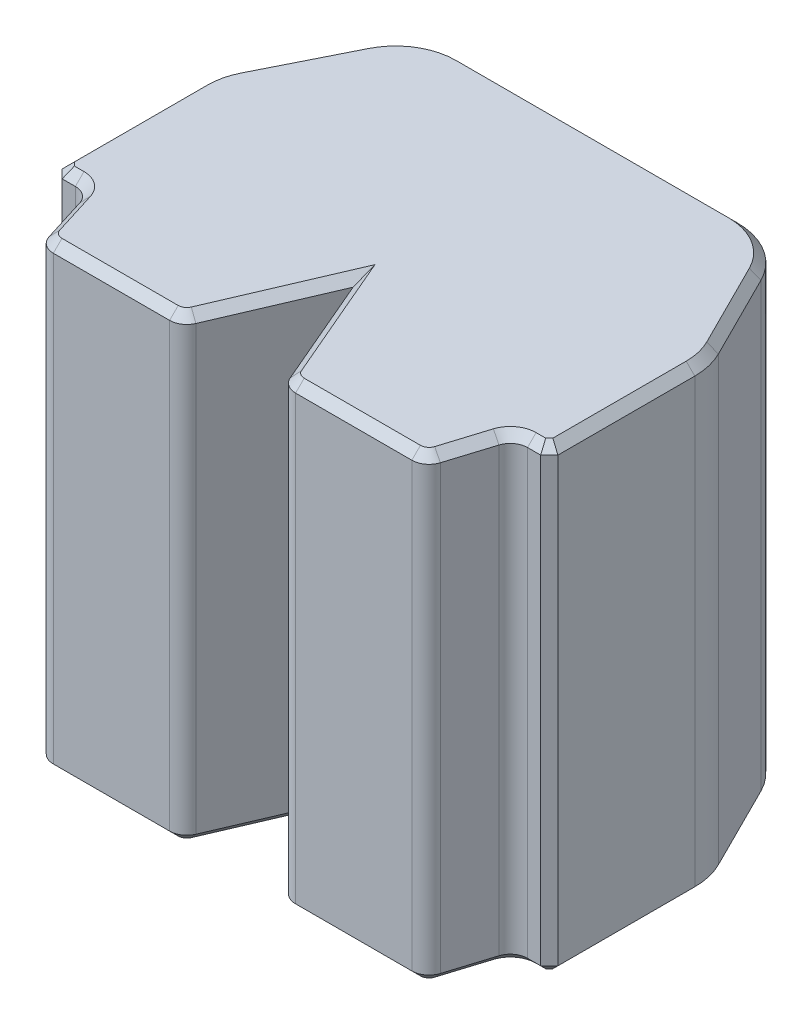
SolidWorks part; units mm, degrees
ref_plane "Front Plane" through (0, 0, 0) normal (0, 0, 1) x (1, 0, 0)
ref_plane "Top Plane" through (0, 0, 0) normal (0, 1, 0) x (1, 0, 0)
ref_plane "Right Plane" through (0, 0, 0) normal (1, 0, 0) x (0, 0, -1)
sketch "Sketch1" plane through (0, 0, 0) normal (0, 1, 0) x (1, 0, 0)
  line L0 (-10.4, 10.7) -> (-14.4, 2.7)
  line L1 (-14.4, -10.7) -> (14.4, -10.7)
  line L2 (-14.4, -10.7) -> (-14.4, 10.7)
  line L3 (-14.4, 10.7) -> (14.4, 10.7)
  line L4 (14.4, -10.7) -> (14.4, 10.7)
  line L5 (10.4, 10.7) -> (14.4, 2.7)
  line L6 (14.4, -6.7) -> (12.4, -6.7)
  line L7 (12.4, -6.7) -> (11.15, -10.7)
  line L8 (-14.4, -6.7) -> (-12.4, -6.7)
  line L9 (-12.4, -6.7) -> (-11.15, -10.7)
  line L10 (-3, -10.7) -> (0, -3.7)
  line L11 (0, -3.7) -> (3, -10.7)
  point P12 (14.4, 0)
  point P14 (0, 10.7)
  point P20 (0, 0)
  dimension "D1" = 21.4
  dimension "D2" = 28.8
  dimension "D3" = 4
  dimension "D4" = 8
  dimension "D5" = 4
  dimension "D6" = 8
  dimension "D7" = 2
  dimension "D8" = 4
  dimension "D9" = 3.25
  dimension "D10" = 3.25
  dimension "D11" = 2
  dimension "D12" = 7
  dimension "D13" = 6
extrude "Boss-Extrude1" add sketch "Sketch1" along normal blind 26.7 contours L10 L11 L1 L7 L6 L4 L5 L3 L0 L2 L8 L9
fillet "Fillet1" radius 4 4 edges at (-14.4, 13.35, -2.7) (14.4, 13.35, -2.7) (10.4, 13.35, -10.7) (-10.4, 13.35, -10.7)
fillet "Fillet2" radius 1 6 edges at (-3, 13.35, 10.7) (3, 13.35, 10.7) (11.15, 13.35, 10.7) (12.4, 13.35, 6.7) (-12.4, 13.35, 6.7) (-11.15, 13.35, 10.7)
chamfer "Chamfer1" distance 0.5 angle 45 2 edges at (-14.4, 13.35, 6.7) (14.4, 13.35, 6.7)
chamfer "Chamfer2" distance 0.5 angle 45 50 edges at (-14.293, 26.7, -2.6747) (-12.7416, 26.7, -6.0167) (-10.0308, 26.7, -10.1026) (0, 26.7, -10.7) (10.0308, 26.7, -10.1026) (12.7416, 26.7, -6.0167) (14.293, 26.7, -2.6747) (14.4, 26.7, 2.2221) (14.15, 26.7, 6.45) (13.5176, 26.7, 6.7) (12.5429, 26.7, 6.8943) (11.775, 26.7, 8.7) (11.0071, 26.7, 10.5057) (7.0371, 26.7, 10.7) (3.1089, 26.7, 10.5348) (1.3701, 26.7, 6.897) (-1.3701, 26.7, 6.897) (-3.1089, 26.7, 10.5348) (-7.0371, 26.7, 10.7) (-11.0071, 26.7, 10.5057) (-11.775, 26.7, 8.7) (-12.5429, 26.7, 6.8943) (-13.5176, 26.7, 6.7) (-14.15, 26.7, 6.45) (-14.4, 26.7, 2.2221) (-12.5429, 0, 6.8943) (-11.775, 0, 8.7) (-11.0071, 0, 10.5057) (-7.0371, 0, 10.7) (-3.1089, 0, 10.5348) (-1.3701, 0, 6.897) (1.3701, 0, 6.897) (3.1089, 0, 10.5348) (7.0371, 0, 10.7) (11.0071, 0, 10.5057) (11.775, 0, 8.7) (12.5429, 0, 6.8943) (13.5176, 0, 6.7) (14.15, 0, 6.45) (14.4, 0, 2.2221) (14.293, 0, -2.6747) (12.7416, 0, -6.0167) (10.0308, 0, -10.1026) (0, 0, -10.7) (-10.0308, 0, -10.1026) (-12.7416, 0, -6.0167) (-14.293, 0, -2.6747) (-14.4, 0, 2.2221) (-14.15, 0, 6.45) (-13.5176, 0, 6.7)
sketch "Sketch2" plane through (0, 0, -10.7) normal (0, 0, -1) x (-1, 0, 0)
  line L0 (-4, 22.15) -> (-4, 17.75) construction
  line L1 (-4, 17.75) -> (-4, 13.35) construction
  line L2 (-4, 13.35) -> (-4, 8.95) construction
  line L3 (4, 22.15) -> (4, 17.75) construction
  line L4 (4, 17.75) -> (4, 13.35) construction
  line L5 (4, 13.35) -> (4, 8.95) construction
  line L6 (-4, 8.95) -> (-4, 4.55) construction
  line L7 (4, 8.95) -> (4, 4.55) construction
  line L8 (-4, 22.15) -> (4, 4.55) construction
  line L9 (4, 22.15) -> (-4, 4.55) construction
  line L10 (-13.9777, 26.2) -> (-13.9777, 0.5) construction
  circle A0 centre (-4, 22.15) radius 2
  circle A1 centre (4, 22.15) radius 2
  circle A2 centre (-4, 17.75) radius 2
  circle A3 centre (4, 17.75) radius 2
  circle A4 centre (-4, 13.35) radius 2
  circle A5 centre (4, 13.35) radius 2
  circle A6 centre (-4, 8.95) radius 2
  circle A7 centre (4, 8.95) radius 2
  circle A8 centre (-4, 4.55) radius 2
  circle A9 centre (4, 4.55) radius 2
  point P20 (0, 13.35)
  point P24 (-13.9777, 13.35)
  dimension "D1" = 4
  dimension "D2" = 8
  dimension "D3" = 4.4
extrude "Cut-Extrude1" cut sketch "Sketch2" against normal blind 12
